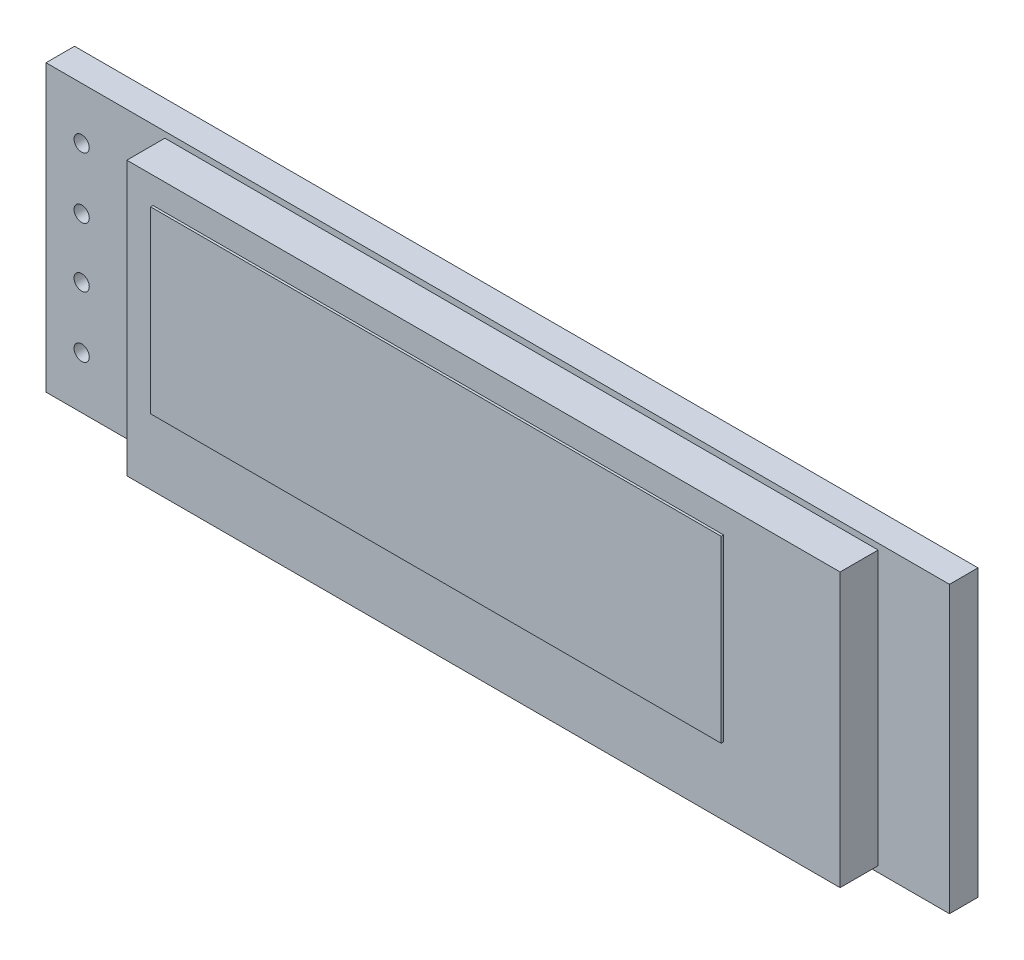
SolidWorks part; units mm, degrees
ref_plane "Front Plane" through (0, 0, 0) normal (0, 0, 1) x (1, 0, 0)
ref_plane "Top Plane" through (0, 0, 0) normal (0, 1, 0) x (1, 0, 0)
ref_plane "Right Plane" through (0, 0, 0) normal (1, 0, 0) x (0, 0, -1)
sketch "Sketch1" plane through (0, 0, 0) normal (0, 0, 1) x (1, 0, 0)
  line L1 (19, -6) -> (-19, -6)
  line L2 (19, -6) -> (19, 6)
  line L3 (19, 6) -> (-19, 6)
  line L4 (-19, -6) -> (-19, 6)
  line L5 (19, -6) -> (-19, 6) construction
  line L6 (19, 6) -> (-19, -6) construction
  point P0 (0, 0)
  dimension "D1" = 38
  dimension "D2" = 12
extrude "Boss-Extrude1" add sketch "Sketch1" along normal blind 1.2
sketch "Sketch2" plane through (0, 0, 1.2) normal (0, 0, 1) x (1, 0, 0)
  line L0 (-19, 6) -> (-19, -6) construction
  line L1 (-14, -5.75) -> (16, -5.75)
  line L2 (-14, -5.75) -> (-14, 5.75)
  line L3 (-14, 5.75) -> (16, 5.75)
  line L4 (16, -5.75) -> (16, 5.75)
  line L5 (-14, -5.75) -> (16, 5.75) construction
  line L6 (-14, 5.75) -> (16, -5.75) construction
  line L7 (-19, 0) -> (19, 0) construction
  line L8 (19, -6) -> (19, 6) construction
  point P0 (1, 0)
  dimension "D1" = 5
  dimension "D2" = 11.5
  dimension "D3" = 30
extrude "Boss-Extrude2" add sketch "Sketch2" along normal blind 1.6
sketch "Sketch4" plane through (0, 0, 2.8) normal (0, 0, 1) x (1, 0, 0)
  line L0 (-14, 0) -> (16, 0) construction
  line L1 (-14, 5.75) -> (-14, -5.75) construction
  line L2 (16, -5.75) -> (16, 5.75) construction
  line L3 (-19, 6) -> (-19, -6) construction
  line L4 (-12.9, 4.65) -> (11.1, 4.65)
  line L5 (-12.9, 4.65) -> (-12.9, -2.89)
  line L6 (-12.9, -2.89) -> (11.1, -2.89)
  line L7 (11.1, 4.65) -> (11.1, -2.89)
  line L8 (-12.9, 4.65) -> (11.1, -2.89) construction
  line L9 (-12.9, -2.89) -> (11.1, 4.65) construction
  line L10 (16, 5.75) -> (-14, 5.75) construction
  point P6 (-0.9, 0.88)
  dimension "D1" = 7.54
  dimension "D2" = 24
  dimension "D3" = 6.1
  dimension "D4" = 1.1
sketch "Sketch5" plane through (0, 0, 0) normal (0, 0, -1) x (-1, 0, 0)
  line L0 (17.5, 6) -> (17.5, -6) construction
  line L1 (-19, 6) -> (19, 6) construction
  line L2 (19, -6) -> (-19, -6) construction
  line L3 (19, 6) -> (19, -6) construction
  circle A0 centre (17.5, 3.81) radius 0.32
  circle A1 centre (17.5, 1.25) radius 0.32
  circle A2 centre (17.5, -1.25) radius 0.32
  circle A3 centre (17.5, -3.81) radius 0.32
  dimension "D2" = 0.64
  dimension "D1" = 1.5
  dimension "D3" = 7.62
  dimension "D4" = 2.56
  dimension "D5" = 2.56
  dimension "D6" = 2.19
extrude "Boss-Extrude6" add sketch "Sketch4" along normal blind 0.1
extrude "Cut-Extrude1" cut sketch "Sketch5" against normal up to surface (1.2 mm away) up to face at (1, 0, 1.2)
